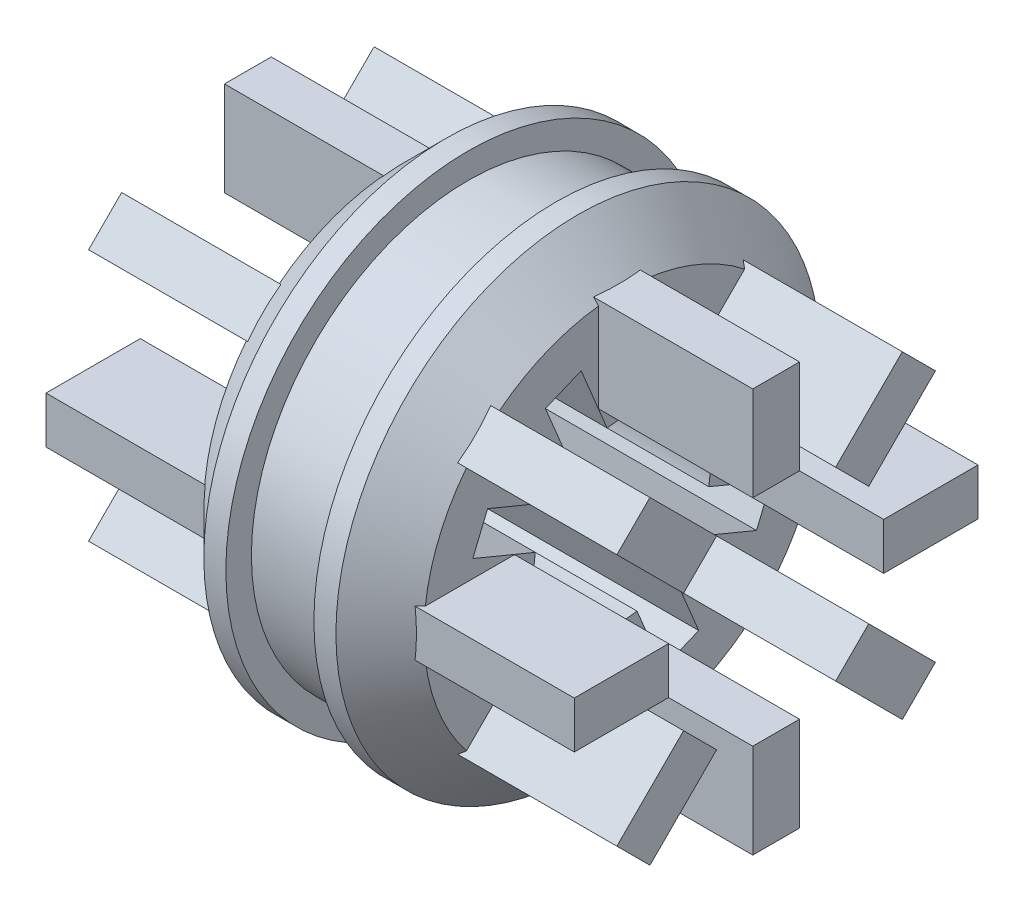
SolidWorks part; units mm, degrees
ref_plane "Front Plane" through (0, 0, 0) normal (0, 0, 1) x (1, 0, 0)
ref_plane "Top Plane" through (0, 0, 0) normal (0, 1, 0) x (1, 0, 0)
ref_plane "Right Plane" through (0, 0, 0) normal (1, 0, 0) x (0, 0, -1)
sketch "Sketch1" plane through (0, 0, 0) normal (1, 0, 0) x (0, 0, -1)
  line L0 (-3.6178, -2.8667) -> (-2.103, -1.3519)
  line L1 (-0.5311, -4.5853) -> (0.5311, -4.5853)
  line L2 (-0.5311, -4.5853) -> (-0.5311, -2.4429)
  line L3 (-0.5311, -2.4429) -> (0.5311, -2.4429)
  line L4 (0.5311, -4.5853) -> (0.5311, -2.4429)
  line L5 (-0.5311, -4.5853) -> (0.5311, -2.4429) construction
  line L6 (-0.5311, -2.4429) -> (0.5311, -4.5853) construction
  line L7 (-3.6178, -2.8667) -> (-2.8667, -3.6178)
  line L8 (-2.8667, -3.6178) -> (-1.3519, -2.103)
  line L9 (-2.103, -1.3519) -> (-1.3519, -2.103)
  line L10 (-4.5853, 0.5311) -> (-2.4429, 0.5311)
  line L11 (-4.5853, 0.5311) -> (-4.5853, -0.5311)
  line L12 (-4.5853, -0.5311) -> (-2.4429, -0.5311)
  line L13 (-2.4429, 0.5311) -> (-2.4429, -0.5311)
  line L14 (-2.8667, 3.6178) -> (-1.3519, 2.103)
  line L15 (-2.8667, 3.6178) -> (-3.6178, 2.8667)
  line L16 (-3.6178, 2.8667) -> (-2.103, 1.3519)
  line L17 (-1.3519, 2.103) -> (-2.103, 1.3519)
  line L18 (0.5311, 4.5853) -> (0.5311, 2.4429)
  line L19 (0.5311, 4.5853) -> (-0.5311, 4.5853)
  line L20 (-0.5311, 4.5853) -> (-0.5311, 2.4429)
  line L21 (0.5311, 2.4429) -> (-0.5311, 2.4429)
  line L22 (3.6178, 2.8667) -> (2.103, 1.3519)
  line L23 (3.6178, 2.8667) -> (2.8667, 3.6178)
  line L24 (2.8667, 3.6178) -> (1.3519, 2.103)
  line L25 (2.103, 1.3519) -> (1.3519, 2.103)
  line L26 (4.5853, -0.5311) -> (2.4429, -0.5311)
  line L27 (4.5853, -0.5311) -> (4.5853, 0.5311)
  line L28 (4.5853, 0.5311) -> (2.4429, 0.5311)
  line L29 (2.4429, -0.5311) -> (2.4429, 0.5311)
  line L30 (2.8667, -3.6178) -> (1.3519, -2.103)
  line L31 (2.8667, -3.6178) -> (3.6178, -2.8667)
  line L32 (3.6178, -2.8667) -> (2.103, -1.3519)
  line L33 (1.3519, -2.103) -> (2.103, -1.3519)
  point P0 (0, -3.5141)
  point P38 (0, 0)
  dimension "D1" = 8
sketch "Sketch2" plane through (0, 0, 0) normal (1, 0, 0) x (0, 0, -1)
  circle A0 centre (0, 0) radius 2.5
  circle A1 centre (0, 0) radius 3.5
  dimension "D1" = 5
  dimension "D2" = 7
sketch "Sketch3" plane through (0, 0, 0) normal (0, 1, 0) x (1, 0, 0)
  line L0 (1, 5.5) -> (1.5, 5.5)
  line L2 (-2.5, 2) -> (-2.5, 4.5)
  line L3 (-1.5, 5.5) -> (-1, 5.5)
  line L4 (2.5, 2) -> (2.5, 4.5)
  line L6 (-1, 5.5) -> (-1, 4.9194)
  line L7 (-1, 4.9194) -> (1, 4.9194)
  line L8 (1, 5.5) -> (1, 4.9194)
  line L9 (-2.5, 2) -> (2.5, 2)
  line L10 (0, 0) -> (6.5963, 0) construction
  line L11 (-2.5, 4.5) -> (-1.5, 5.5)
  line L12 (1.5, 5.5) -> (2.5, 4.5)
  point P1 (2.5, 5.5)
  point P2 (-2.5, 5.5)
  point P10 (0, 4.9194)
  dimension "D1" = 5.5
  dimension "D3" = 2
revolve "Revolve1" add sketch "Sketch3" angle 360 about L10
extrude "Boss-Extrude3" add sketch "Sketch1" along normal mid plane 12
sketch "Sketch4" plane through (0, 0, 0) normal (1, 0, 0) x (0, 0, -1)
  line L0 (1.7413, 3.054) -> (1.129, 1.5758)
  line L1 (1.7413, 3.054) -> (0.9283, 3.3908)
  line L2 (1.129, 1.5758) -> (0.316, 1.9126)
  line L4 (0.9283, 3.3908) -> (0.316, 1.9126)
  line L5 (3.3908, 0.9283) -> (1.9126, 0.316)
  line L6 (0, 0) -> (2.3775, 5.7398) construction
  line L7 (-0.5311, 2.4429) -> (-0.5311, 4.4685) construction
  line L8 (3.3908, 0.9283) -> (3.054, 1.7413)
  line L9 (1.9126, 0.316) -> (1.5758, 1.129)
  line L10 (3.054, 1.7413) -> (1.5758, 1.129)
  line L11 (3.054, -1.7413) -> (1.5758, -1.129)
  line L12 (3.054, -1.7413) -> (3.3908, -0.9283)
  line L13 (1.5758, -1.129) -> (1.9126, -0.316)
  line L14 (3.3908, -0.9283) -> (1.9126, -0.316)
  line L15 (0.9283, -3.3908) -> (0.316, -1.9126)
  line L16 (0.9283, -3.3908) -> (1.7413, -3.054)
  line L17 (0.316, -1.9126) -> (1.129, -1.5758)
  line L18 (1.7413, -3.054) -> (1.129, -1.5758)
  line L19 (-1.7413, -3.054) -> (-1.129, -1.5758)
  line L20 (-1.7413, -3.054) -> (-0.9283, -3.3908)
  line L21 (-1.129, -1.5758) -> (-0.316, -1.9126)
  line L22 (-0.9283, -3.3908) -> (-0.316, -1.9126)
  line L23 (-3.3908, -0.9283) -> (-1.9126, -0.316)
  line L24 (-3.3908, -0.9283) -> (-3.054, -1.7413)
  line L25 (-1.9126, -0.316) -> (-1.5758, -1.129)
  line L26 (-3.054, -1.7413) -> (-1.5758, -1.129)
  line L27 (-3.054, 1.7413) -> (-1.5758, 1.129)
  line L28 (-3.054, 1.7413) -> (-3.3908, 0.9283)
  line L29 (-1.5758, 1.129) -> (-1.9126, 0.316)
  line L30 (-3.3908, 0.9283) -> (-1.9126, 0.316)
  line L31 (-0.9283, 3.3908) -> (-0.316, 1.9126)
  line L32 (-0.9283, 3.3908) -> (-1.7413, 3.054)
  line L33 (-0.316, 1.9126) -> (-1.129, 1.5758)
  line L34 (-1.7413, 3.054) -> (-1.129, 1.5758)
  point P12 (0.7225, 1.7442)
  point P42 (0, 0)
  dimension "D1" = 0.88
  dimension "D2" = 22.5
  dimension "D3" = 1.6
  dimension "D4" = 8
extrude "Cut-Extrude1" cut sketch "Sketch4" against normal through all both and the other way through all
